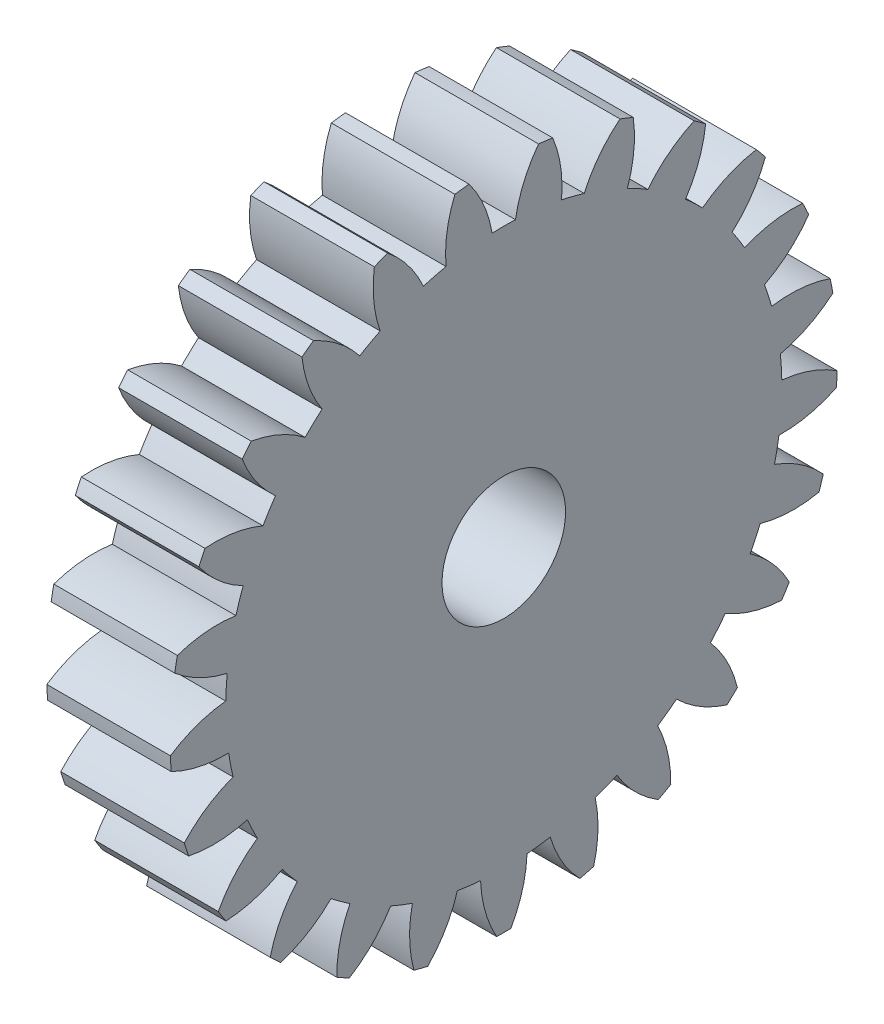
SolidWorks part; units mm, degrees
ref_plane "Plane1" through (0, 0, 0) normal (0, 0, 1) x (1, 0, 0)
ref_plane "Plane2" through (0, 0, 0) normal (0, 1, 0) x (1, 0, 0)
ref_plane "Plane3" through (0, 0, 0) normal (1, 0, 0) x (0, 0, -1)
other "Configuration Table"
sketch "HoldingSke" plane through (0, 0, 0) normal (0, 1, 0) x (1, 0, 0)
  line L0 (0, 0) -> (0.4532, -0.2113)
  line L1 (-15, 0) -> (100, 0) construction
  line L2 (0, 0) -> (-2.1039, 2.3779)
  line L3 (0, 0) -> (-11.863, 4.5341)
  line L4 (0, 0) -> (7.8269, 3.6497)
  line L5 (0, 0) -> (-46.8476, -17.4728)
  line L6 (0, 0) -> (-8.2896, -5.593)
  line L7 (-2.1039, 2.3779) -> (8.6586, 51.2059)
  line L8 (-76.2, 54.61) -> (-74.4, 54.61)
  line L9 (-71.009, 38.7566) -> (-53.1078, 45.2721)
  line L10 (-76.2, 71.12) -> (104.1128, 71.12)
  line L11 (0, 0) -> (-10, 0)
  line L12 (-76.2, 101.6) -> (-76.133, 101.6)
  line L13 (24.9733, 27.94) -> (52.9518, 28.4284)
  line L14 (24.9733, 27.94) -> (24.9743, 27.94)
  line L15 (24.9733, 27.94) -> (100.4006, 29.5858)
  line L16 (-63.627, -2) -> (-12.827, -2)
  circle A0 centre (0, 0) radius 5
  circle A1 centre (0, 0) radius 22.499
  circle A2 centre (0, 0) radius 37.5
  circle A3 centre (0, 0) radius 5
  dimension "MHD" = 44.998
  dimension "Hub_dia" = 75
  dimension "Bore" = 10
  dimension "MBD" = 10
  dimension "Num_teeth" = 25
  dimension "Pitch" = 0.5
  dimension "Overall_len" = 50
  dimension "Show_teeth" = 25
  dimension "Thickness" = 10
  dimension "OAL" = 50.0001
  dimension "T_dim" = 1.8
  dimension "Ap" = 20
  dimension "H" = 19.05
  dimension "Pitch_radius" = 180.3128
  dimension "Width" = 10
  dimension "Backlash" = 0.067
  dimension "Addendum_fac" = 1
  dimension "Dedendum_fac" = 1.25
  dimension "Clearance_fac" = 0.25
  dimension "Dedendum_add" = 0.001
  dimension "Module" = 2
sketch "BasProSke" plane through (0, 0, 0) normal (0, 1, 0) x (1, 0, 0)
  line L0 (-10, 0) -> (60, 0) construction
  line L1 (0, 0) -> (0, 27)
  line L2 (0, 0) -> (10, 0)
  line L3 (10, 0) -> (10, 27)
  line L4 (10, 27) -> (0, 27)
  dimension "Thickness" = 10
  dimension "Diameter" = 54
revolve "Base-Revolve" add sketch "BasProSke" angle 360 about L0
sketch "TooCutSke" plane through (0, 0, 0) normal (1, 0, 0) x (0, 0, -1)
  line L1 (0, 0) -> (0, 107) construction
  line L2 (0, 0) -> (-1.687, 24.943) construction
  line L3 (0, 0) -> (-6.2561, 49.5219) construction
  line L4 (-1.687, 24.943) -> (-3.128, 24.761) construction
  arc A0 (0.9462, 22.4791) -> (-0.9462, 22.4791) centre (0, 0) ccw
  arc A1 (2.8295, 26.8769) -> (-2.8295, 26.8769) centre (0, 0) ccw
  circle A2 centre (0, 0) radius 25 construction
  circle A3 centre (0, 0) radius 23.4923 construction
  arc A4 (-0.9462, 22.4791) -> (-2.8295, 26.8769) centre (-10.8135, 20.8556) ccw
  arc A5 (2.8295, 26.8769) -> (0.9462, 22.4791) centre (10.8135, 20.8556) ccw
  dimension "Root_dia" = 44.998
  dimension "Overcut_dia" = 54.0508
  dimension "Pitch_dia" = 50
  dimension "Base_dia" = 46.9846
  dimension "Flank_rad" = 10
  dimension "Half_ang" = 7.2
  dimension "Half_CT" = 1.4525
extrude "ToothCut" cut sketch "TooCutSke" along normal through all
fillet "Breaks" [suppressed] radius 0.04
fillet "RootFillets" [suppressed] radius 0.501
pattern_circular "TeethCuts" count 25 every 14.4 about axis through (-10, 0, 0) along (1, 0, 0) of "ToothCut", "RootFillets", "Breaks"
sketch "HubNeaOneSke" plane through (0, 0, 0) normal (-1, 0, 0) x (0, 0, 1)
  circle A0 centre (0, 0) radius 22.499
  dimension "Diameter" = 44.998
extrude "HubNearOne" [suppressed] add sketch "HubNeaOneSke" along normal blind 40.0001
sketch "HubNeaBotSke" plane through (0, 0, 0) normal (-1, 0, 0) x (0, 0, 1)
  circle A0 centre (0, 0) radius 22.499
  dimension "Diameter" = 44.998
extrude "HubNearBoth" [suppressed] add sketch "HubNeaBotSke" along normal blind 20
ref_plane "FarPln" through (10, 0, 0) normal (1, 0, 0) x (0, 0, -1)
sketch "HubFarSke" plane through (10, 0, 0) normal (1, 0, 0) x (0, 0, -1)
  circle A0 centre (0, 0) radius 22.499
  dimension "Diameter" = 44.998
extrude "HubFar" [suppressed] add sketch "HubFarSke" along normal blind 20
sketch "BorSke" plane through (0, 0, 0) normal (1, 0, 0) x (0, 0, -1)
  circle A0 centre (0, 0) radius 5
  dimension "Diameter" = 10
extrude "Bore" cut sketch "BorSke" along normal mid plane 100.0001
sketch "KeySke" plane through (0, 0, 0) normal (1, 0, 0) x (0, 0, -1)
  line L0 (-2, 0) -> (-2, 6.8)
  line L1 (-2, 6.8) -> (2, 6.8)
  line L2 (2, 6.8) -> (2, 0)
  line L3 (0, 0) -> (0, 34) construction
  line L4 (-2, 0) -> (2, 0)
  dimension "Offset" = 6.8
  dimension "Width" = 4
extrude "Keyway" [suppressed] cut sketch "KeySke" along normal mid plane 100.0001
pattern_circular "Keyway2" [suppressed] count 2 every 90 about axis through (-10, 0, 0) along (1, 0, 0)
equation "' \"Module@HoldingSke\" = 6.35"
equation "' \"Num_teeth@HoldingSke\" = 12"
equation "' \"Ap@HoldingSke\" =  20"
equation "' \"Ap@HoldingSke\" = 20"
equation "' \"Width@HoldingSke\" = 0.5 * 25.4"
equation "' \"Hub_dia@HoldingSke\"= 1 * 25.4"
equation "' \"Hub_dia@HoldingSke\" = 1 * 25.4"
equation "' \"Overall_len@HoldingSke\" = 1.0 * 25.4"
equation "' \"Bore@HoldingSke\" = 0.75 * 25.4"
equation "' \"T_dim@HoldingSke\" = 0.1 * 25.4"
equation "' \"Width@KeySke\" = 0.25 * 25.4"
equation "' \"Show_teeth@HoldingSke\" = 13"
equation "' \"Backlash@HoldingSke\" = 0.009 * 25.4"
equation "' \"Addendum_fac@HoldingSke\" = 1.0"
equation "' \"Dedendum_fac@HoldingSke\" = 1.25"
equation "' \"Dedendum_add@HoldingSke\" = 0.00005 * 25.4"
equation "' \"Clearance_fac@HoldingSke\" = 0.25"
equation "\"Pitch@HoldingSke\" = 1 / \"Module@HoldingSke\""
equation "\"Overcut_dia@TooCutSke\" = (\"Num_teeth@HoldingSke\" + 2 * \"Addendum_fac@HoldingSke\") / \"Pitch@HoldingSke\" + 0.002 * 25.4"
equation "\"Pitch_dia@TooCutSke\" = \"Num_teeth@HoldingSke\" / \"Pitch@HoldingSke\""
equation "\"Base_dia@TooCutSke\" = \"Num_teeth@HoldingSke\" / \"Pitch@HoldingSke\" * cos((\"Ap@HoldingSke\"  * 3.14159265 / 180))"
equation "\"Root_dia@TooCutSke\" = (\"Num_teeth@HoldingSke\" + 2) / \"Pitch@HoldingSke\" - 2 * (\"Addendum_fac@HoldingSke\" + \"Dedendum_fac@HoldingSke\") / \"Pitch@HoldingSke\" - \"Dedendum_add@HoldingSke\" * 2"
equation "\"Half_ang@TooCutSke\" = 180 / \"Num_teeth@HoldingSke\""
equation "\"Half_CT@TooCutSke\" = \"Num_teeth@HoldingSke\" / \"Pitch@HoldingSke\" * sin((3.14159265 / 2 / \"Num_teeth@HoldingSke\")) / 2 - 7 * \"Backlash@HoldingSke\" / 4"
equation "\"Flank_rad@TooCutSke\" = \"Num_teeth@HoldingSke\" / \"Pitch@HoldingSke\" / 5"
equation "\"Radius@RootFillets\" = \"Clearance_fac@HoldingSke\" / \"Pitch@HoldingSke\" + \"Dedendum_add@HoldingSke\""
equation "\"Break_rad@Breaks\" = 0.02 / \"Pitch@HoldingSke\""
equation "\"Thickness@HoldingSke\" = \"Width@HoldingSke\""
equation "\"OAL@HoldingSke\" = \"Thickness@HoldingSke\""
equation "\"MHD@HoldingSke\" = (\"Num_teeth@HoldingSke\" + 2) / \"Pitch@HoldingSke\" - 2 * (\"Addendum_fac@HoldingSke\" + \"Dedendum_fac@HoldingSke\")  / \"Pitch@HoldingSke\" - \"Dedendum_add@HoldingSke\" * 2"
equation "\"MBD@HoldingSke\" = (\"Num_teeth@HoldingSke\" + 2) / \"Pitch@HoldingSke\" - 2 * (\"Addendum_fac@HoldingSke\" + \"Dedendum_fac@HoldingSke\")  / \"Pitch@HoldingSke\" - \"Dedendum_add@HoldingSke\" * 2 - 0.002 * 25.4"
equation "\"MHD@HoldingSke\" = ((sgn( \"MHD@HoldingSke\" - \"Hub_dia@HoldingSke\" )-1)*( \"MHD@HoldingSke\" - \"Hub_dia@HoldingSke\" ))/-2+ \"Hub_dia@HoldingSke\""
equation "\"MBD@HoldingSke\" = ((sgn( \"MBD@HoldingSke\" - \"Bore@HoldingSke\" )-1)*( \"MBD@HoldingSke\" - \"Bore@HoldingSke\" ))/-2+ \"Bore@HoldingSke\""
equation "\"OAL@HoldingSke\" = ((sgn( \"OAL@HoldingSke\" - \"Overall_len@HoldingSke\" )+1)*( \"OAL@HoldingSke\" - \"Overall_len@HoldingSke\" ))/2 + \"Overall_len@HoldingSke\" + 0.000002 * 25.4"
equation "\"Num_teeth@TeethCuts\" = int( \"Show_teeth@HoldingSke\" ) + 1"
equation "\"Num_teeth@TeethCuts\" = ((sgn( \"Num_teeth@TeethCuts\" - \"Num_teeth@HoldingSke\" )-1)*( \"Num_teeth@TeethCuts\" - \"Num_teeth@HoldingSke\" ))/-2+ \"Num_teeth@HoldingSke\""
equation "\"Num_teeth@TeethCuts\" = ((sgn( \"Num_teeth@TeethCuts\" - 2.0)+1)*( \"Num_teeth@TeethCuts\" - 2.0))/2 +2.0"
equation "\"Angle@TeethCuts\" = 360.0 / \"Num_teeth@HoldingSke\""
equation "\"Diameter@BasProSke\" = (\"Num_teeth@HoldingSke\" + 2 * \"Addendum_fac@HoldingSke\") / \"Pitch@HoldingSke\""
equation "\"Thickness@BasProSke\"  = \"Thickness@HoldingSke\""
equation "' \"Fillet_rad@BasProSke\" =  \"Thickness@HoldingSke\" * 0.05"
equation "' \"Fillet_rad@BasProSke\" = \"Thickness@HoldingSke\" * 0.05"
equation "\"MHD@HoldingSke\" = ((sgn( \"MHD@HoldingSke\" - \"Root_dia@TooCutSke\" )-1)*( \"MHD@HoldingSke\" - \"Root_dia@TooCutSke\" ))/-2+ \"Root_dia@TooCutSke\""
equation "\"Diameter@HubNeaOneSke\" = \"MHD@HoldingSke\""
equation "\"Length@HubNearOne\" = \"OAL@HoldingSke\" - \"Thickness@BasProSke\""
equation "\"Diameter@HubNeaBotSke\" = \"MHD@HoldingSke\""
equation "\"Length@HubNearBoth\" = ( \"OAL@HoldingSke\" - \"Thickness@BasProSke\" ) / 2.0"
equation "\"Thickness@FarPln\" = \"Thickness@BasProSke\""
equation "\"Diameter@HubFarSke\" = \"MHD@HoldingSke\""
equation "\"Length@HubFar\" = ( \"OAL@HoldingSke\" - \"Thickness@BasProSke\" ) / 2.0"
equation "\"Diameter@BorSke\" = \"MBD@HoldingSke\""
equation "\"D1@Bore\" = \"OAL@HoldingSke\" * 2.0"
equation "\"D1@Keyway\" = \"OAL@HoldingSke\" * 2.0"
equation "\"Offset@KeySke\" = \"T_dim@HoldingSke\" + \"MBD@HoldingSke\" / 2.0"
